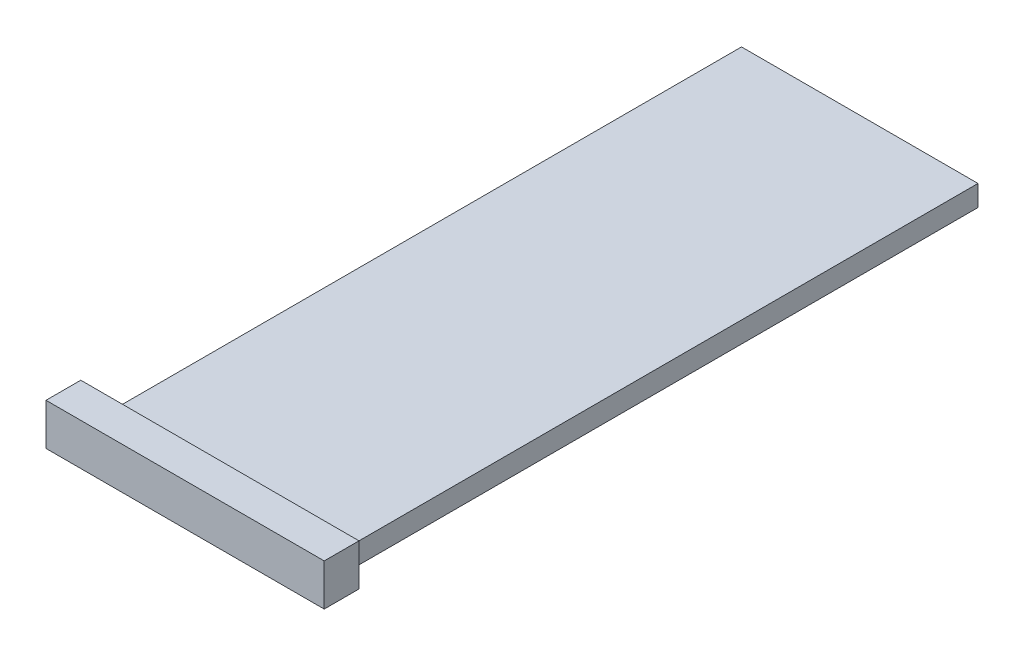
SolidWorks part; units mm, degrees
ref_plane "Front Plane" through (0, 0, 0) normal (0, 0, 1) x (1, 0, 0)
ref_plane "Top Plane" through (0, 0, 0) normal (0, 1, 0) x (1, 0, 0)
ref_plane "Right Plane" through (0, 0, 0) normal (1, 0, 0) x (0, 0, -1)
sketch "Sketch1" plane through (0, 0, 0) normal (0, 0, 1) x (1, 0, 0)
  line L1 (-40.1026, 12.4667) -> (-6.1026, 12.4667)
  line L2 (-40.1026, 12.4667) -> (-40.1026, 6.4667)
  line L3 (-40.1026, 6.4667) -> (-6.1026, 6.4667)
  line L4 (-6.1026, 12.4667) -> (-6.1026, 6.4667)
  dimension "D1" = 34
  dimension "D2" = 6
extrude "Boss-Extrude1" add sketch "Sketch1" against normal blind 5
ref_plane "Plane1" through (0, 0, -5) normal (0, 0, -1) x (-1, 0, 0)
sketch "Sketch2" plane through (0, 0, -5) normal (0, 0, -1) x (-1, 0, 0)
  line L0 (40.1026, 12.4667) -> (40.1026, 6.4667) construction
  line L1 (6.1026, 6.4667) -> (40.1026, 6.4667)
  line L2 (6.1026, 6.4667) -> (6.1026, 9.4667)
  line L3 (6.1026, 9.4667) -> (40.1026, 9.4667)
  line L4 (40.1026, 6.4667) -> (40.1026, 9.4667)
extrude "Boss-Extrude2" add sketch "Sketch2" along normal blind 92
sketch "Sketch3" plane through (-40.1026, 0, 0) normal (-1, 0, 0) x (0, 0, 1)
  line L0 (-5, 9.4667) -> (-5, 6.4667)
  line L1 (-97, 6.4667) -> (0, 6.4667) construction
  line L2 (-5, 9.4667) -> (-5, 12.4667)
  line L3 (-5, 12.4667) -> (0, 12.4667)
  line L4 (0, 12.4667) -> (0, 6.4667)
  line L5 (0, 6.4667) -> (-5, 6.4667)
extrude "Boss-Extrude3" add sketch "Sketch3" along normal blind 3
sketch "Sketch4" plane through (-6.1026, 0, 0) normal (1, 0, 0) x (0, 0, -1)
  line L0 (97, 6.4667) -> (0, 6.4667) construction
  line L1 (0, 12.4667) -> (5.0014, 12.4667)
  line L2 (0, 12.4667) -> (0, 6.4667)
  line L3 (0, 6.4667) -> (5.0014, 6.4667)
  line L4 (5.0014, 12.4667) -> (5.0014, 6.4667)
extrude "Boss-Extrude4" add sketch "Sketch4" along normal blind 3
